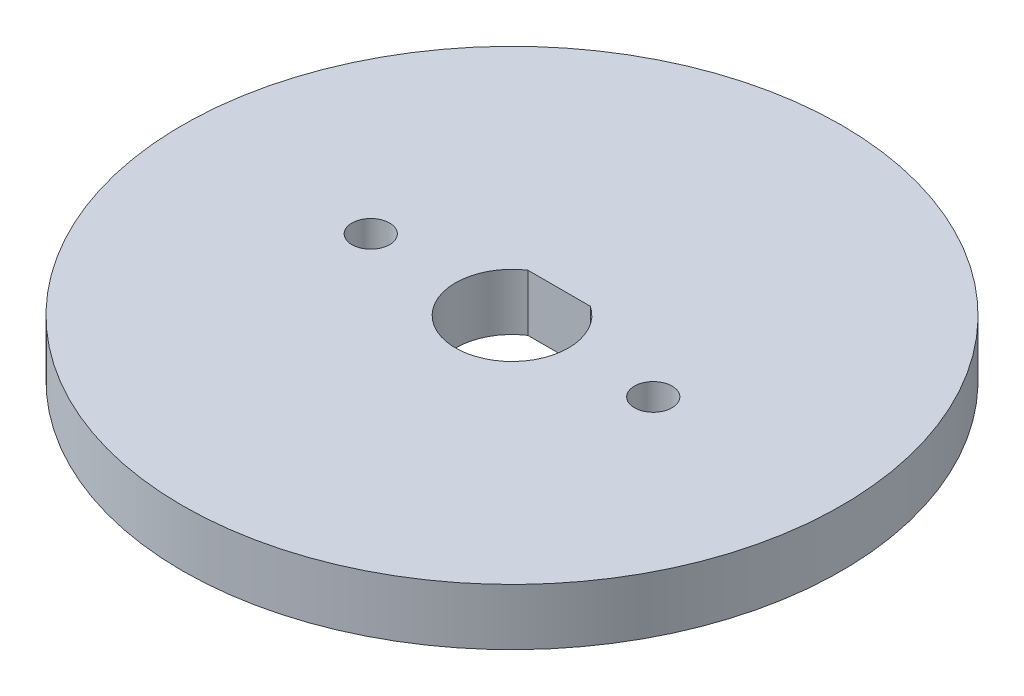
SolidWorks part; units mm, degrees
material "Kiefer"
ref_plane "Ebene vorne" through (0, 0, 0) normal (0, 0, 1) x (1, 0, 0)
ref_plane "Ebene oben" through (0, 0, 0) normal (0, 1, 0) x (1, 0, 0)
ref_plane "Ebene rechts" through (0, 0, 0) normal (1, 0, 0) x (0, 0, -1)
sketch "Skizze1" plane through (0, 0, 0) normal (0, 1, 0) x (1, 0, 0)
  circle A0 centre (0, 0) radius 17.5
  dimension "D1" = 35
extrude "Aufsatz-Linear austragen1" add sketch "Skizze1" along normal blind 3
sketch "Skizze2" plane through (0, 3, 0) normal (0, 1, 0) x (1, 0, 0)
  line L0 (-1.6583, 2.5) -> (1.6583, 2.5)
  line L1 (7.5, 0) -> (-7.5, 0) construction
  arc A0 (-1.6583, 2.5) -> (1.6583, 2.5) centre (0, 0) ccw
  circle A1 centre (-7.5, 0) radius 1
  circle A2 centre (7.5, 0) radius 1
  point P8 (0, 0)
  dimension "D1" = 3
  dimension "D3" = 2
  dimension "D2" = 2.5
  dimension "D4" = 15
extrude "Schnitt-Linear austragen1" cut sketch "Skizze2" against normal through all
